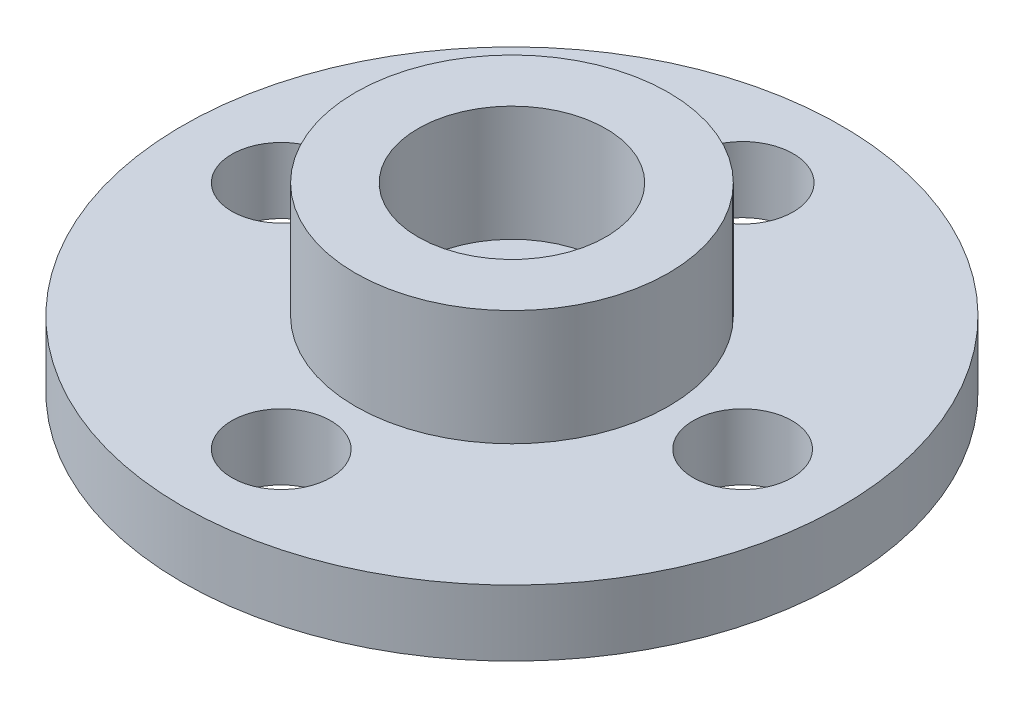
SolidWorks part; units mm, degrees
ref_plane "Alzado" through (0, 0, 0) normal (0, 0, 1) x (1, 0, 0)
ref_plane "Planta" through (0, 0, 0) normal (0, 1, 0) x (1, 0, 0)
ref_plane "Vista lateral" through (0, 0, 0) normal (1, 0, 0) x (0, 0, -1)
sketch "Croquis1" plane through (0, 0, 0) normal (0, 1, 0) x (1, 0, 0)
  circle A0 centre (0, 0) radius 10
  circle A1 centre (0, 0) radius 2.75
  circle A2 centre (0, 7) radius 1.5335
  circle A3 centre (7, 0) radius 1.5
  circle A4 centre (0, -7) radius 1.5
  circle A5 centre (-7, 0) radius 1.5
  circle A6 centre (0, 0) radius 1.5
  dimension "D1" = 20
  dimension "D2" = 5.5
  dimension "D3" = 7
  dimension "D4" = 14
  dimension "D5" = 7
  dimension "D6" = 14
extrude "Saliente-Extruir1" add sketch "Croquis1" along normal blind 2 contours A0 A5 A4 A3 A2 A1 | A1 A6
sketch "Croquis2" plane through (0, 2, 0) normal (0, 1, 0) x (1, 0, 0)
  circle A0 centre (0, 0) radius 2.85
  circle A1 centre (0, 0) radius 1.5
  circle A2 centre (0, 0) radius 4.75
  dimension "D1" = 5.7
extrude "Saliente-Extruir2" add sketch "Croquis2" along normal blind 3.5 contours A2 A0
sketch "Croquis3" plane through (0, 0, 0) normal (0, -1, 0) x (1, 0, 0)
